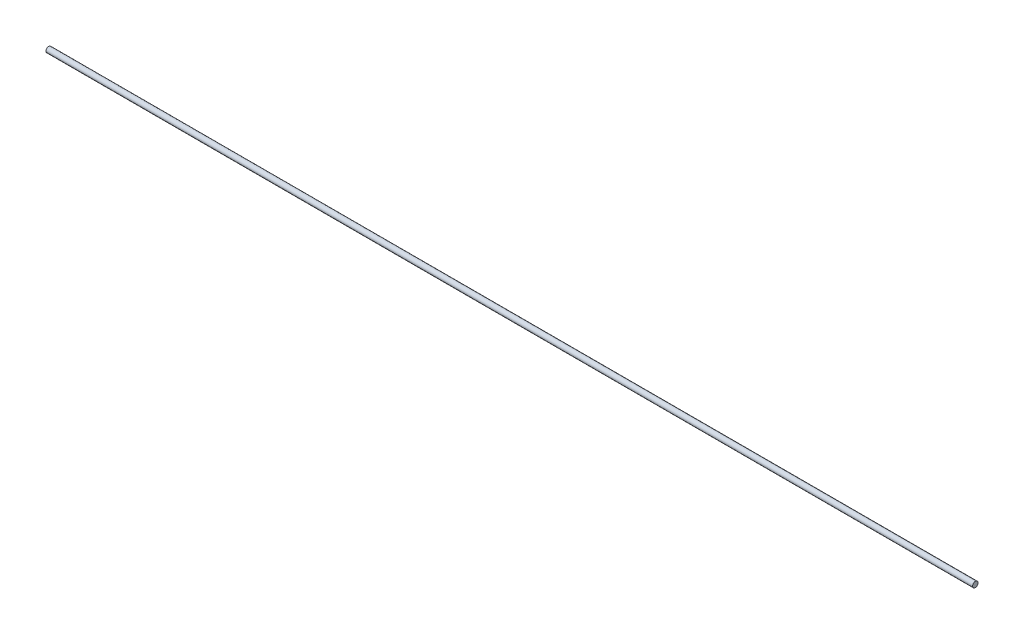
SolidWorks part; units mm, degrees
ref_plane "前视基准面" through (0, 0, 0) normal (0, 0, 1) x (1, 0, 0)
ref_plane "上视基准面" through (0, 0, 0) normal (0, 1, 0) x (1, 0, 0)
ref_plane "右视基准面" through (0, 0, 0) normal (1, 0, 0) x (0, 0, -1)
sketch "草图1" plane through (0, 0, 0) normal (0, 0, 1) x (1, 0, 0)
  line L0 (0, 0) -> (340, 0)
  dimension "D1" = 340
sketch "草图2" plane through (0, 0, 0) normal (1, 0, 0) x (0, 0, -1)
  circle A0 centre (0, 0) radius 1
  point P2 (2.2101, 0)
  point P3 (0, 0)
  point P4 (0, 0)
  dimension "D1" = 2
sweep "扫描1" add profiles "草图2" path "草图1"
